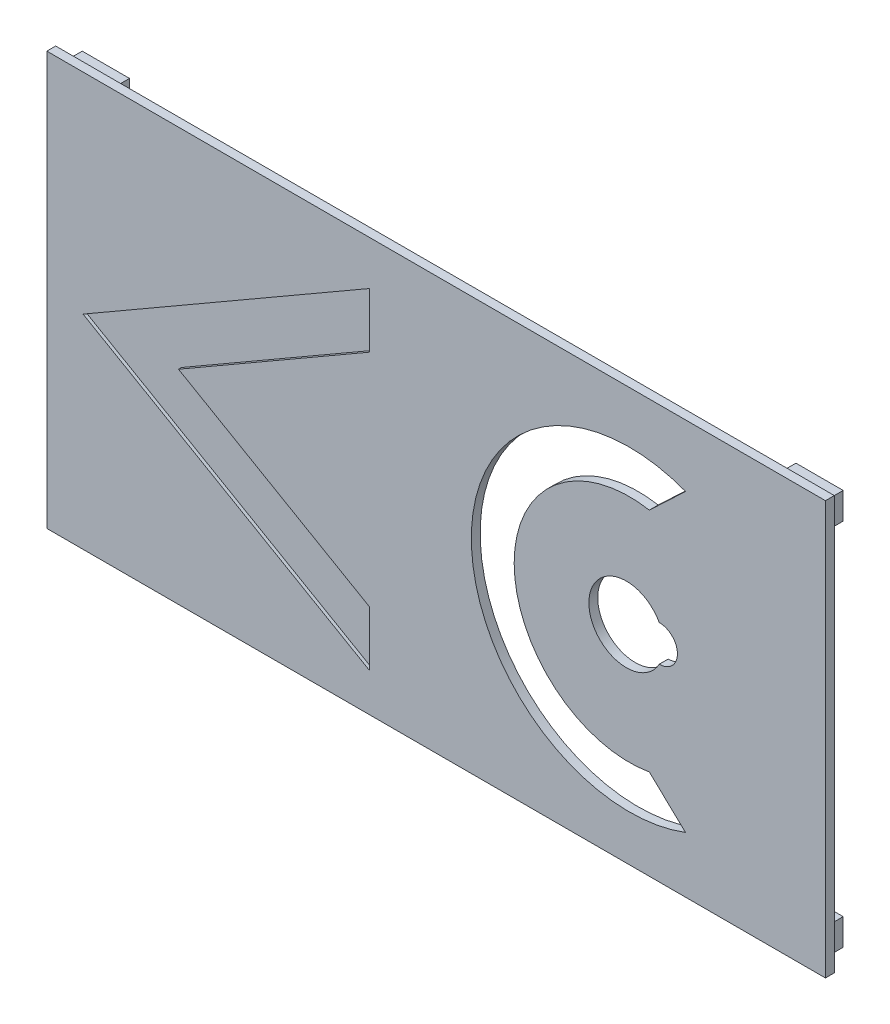
SolidWorks part; units mm, degrees
ref_plane "Front Plane" through (0, 0, 0) normal (0, 0, 1) x (1, 0, 0)
ref_plane "Top Plane" through (0, 0, 0) normal (0, 1, 0) x (1, 0, 0)
ref_plane "Right Plane" through (0, 0, 0) normal (1, 0, 0) x (0, 0, -1)
sketch "Sketch1" plane through (0, 0, 0) normal (0, 0, 1) x (1, 0, 0)
  line L0 (121.1, -9.75) -> (-10.75, -9.75)
  line L1 (119.6, -8.25) -> (-9.25, -8.25)
  line L2 (119.6, -8.25) -> (119.6, 58.75)
  line L3 (119.6, 58.75) -> (-9.25, 58.75)
  line L4 (-9.25, -8.25) -> (-9.25, 58.75)
  line L5 (-10.75, -9.75) -> (-10.75, 60.25)
  line L6 (121.1, 60.25) -> (-10.75, 60.25)
  line L7 (121.1, -9.75) -> (121.1, 60.25)
  dimension "D1" = 1.5
extrude "Boss-Extrude1" add sketch "Sketch1" along normal blind 1.5 contours L7 L6 L5 L0
sketch "Sketch2" plane through (0, 0, 1.5) normal (0, 0, 1) x (1, 0, 0)
  line L5 (92.9571, 22.2) -> (92.9875, 22.2)
  line L6 (92.9875, 28.3) -> (92.9571, 28.3)
  line L7 (92.9571, 22.2) -> (92.9875, 22.2)
  line L8 (92.9875, 28.3) -> (92.9571, 28.3)
  arc A10 (92.9875, 22.2) -> (92.9875, 28.3) centre (92.9875, 25.25) ccw
  arc A11 (92.9571, 28.3) -> (92.9571, 22.2) centre (87.3875, 25.25) ccw
  arc A12 (92.9875, 22.2) -> (92.9875, 28.3) centre (92.9875, 25.25) ccw
  arc A13 (92.9571, 28.3) -> (92.9571, 22.2) centre (87.3875, 25.25) ccw
  dimension "D1" = 0.25
extrude "Cut-Extrude1" cut sketch "Sketch2" against normal up to next
ref_plane "Plane2" through (0, 25.25, 0) normal (0, 1, 0) x (1, 0, 0)
ref_plane "Plane1" through (55.175, 0, 0) normal (1, 0, 0) x (0, 0, -1)
sketch "Sketch3" plane through (121.1, 0, 0) normal (1, 0, 0) x (0, 0, -1)
  line L0 (0, -9.75) -> (0, 60.25) construction
  line L1 (-1.5, 60.25) -> (6, 60.25)
  line L2 (-1.5, 60.25) -> (-1.5, 61.75)
  line L3 (-1.5, 61.75) -> (6, 61.75)
  line L4 (6, 60.25) -> (6, 61.75)
  line L5 (6, 60.25) -> (4.5, 58.75)
  line L7 (4.5, 58.75) -> (4.5, 60.25)
  dimension "D1" = 1.5
  dimension "D2" = 6
  dimension "D3" = 45
sketch "Sketch4" plane through (0, 0, 0) normal (0, 0, -1) x (-1, 0, 0)
  line L0 (-118.1, 57.25) -> (-118.1, 55.75)
  line L1 (-119.6, 58.75) -> (-111.6, 58.75)
  line L2 (-119.6, 58.75) -> (-119.6, 54.25)
  line L3 (-119.6, 54.25) -> (-111.6, 54.25)
  line L4 (-111.6, 58.75) -> (-111.6, 54.25)
  line L5 (-119.6, 58.75) -> (-119.6, 60.25) construction
  line L6 (-118.1, 55.75) -> (-113.1, 55.75)
  line L7 (-121.1, 60.25) -> (10.75, 60.25) construction
  line L8 (-113.1, 57.25) -> (-113.1, 55.75)
  line L9 (-118.1, 57.25) -> (-113.1, 57.25)
  line L10 (-119.6, 58.75) -> (-121.1, 58.75) construction
  line L11 (-121.1, -9.75) -> (-121.1, 60.25) construction
  dimension "D1" = 1.5
  dimension "D2" = 5
  dimension "D3" = 1.5
extrude "Boss-Extrude2" add sketch "Sketch4" along normal blind 3
mirror "Mirror1" about plane through (0, 25.25, 0) normal (0, 1, 0) of "Boss-Extrude2"
mirror "Mirror2" about plane through (55.175, 0, 0) normal (1, 0, 0) of "Mirror1", "Boss-Extrude2"
sketch "Sketch5" plane through (0, 0, 1.5) normal (0, 0, 1) x (1, 0, 0)
  line L0 (62.8875, 28.45) -> (62.8875, 21.05) construction
  line L1 (62.8875, 28.45) -> (62.8875, 21.05) construction
  line L2 (61.3875, 28.45) -> (61.3875, 21.05) construction
  line L3 (61.3875, 28.45) -> (61.3875, 21.05) construction
  line L4 (61.3875, 28.45) -> (62.8875, 28.45) construction
  line L5 (61.3875, 28.45) -> (62.8875, 28.45) construction
  line L6 (61.3875, 21.05) -> (62.8875, 21.05) construction
  line L7 (61.3875, 21.05) -> (62.8875, 21.05) construction
  line L8 (68.3875, 21.05) -> (66.8875, 21.05) construction
  line L9 (68.3875, 28.45) -> (66.8875, 28.45) construction
  line L10 (68.3875, 25.6038) -> (68.3875, 23.8962) construction
  line L11 (91.2742, 5.5464) -> (97.4081, -0.256)
  line L12 (61.3875, 21.05) -> (68.3875, 21.05) construction
  line L13 (61.3875, 21.05) -> (61.3875, 28.45) construction
  line L14 (61.3875, 28.45) -> (68.3875, 28.45) construction
  line L15 (68.3875, 21.05) -> (68.3875, 28.45) construction
  line L16 (84.1875, 51.25) -> (91.5875, 51.25) construction
  line L17 (84.1875, 51.25) -> (84.1875, 44.25) construction
  line L18 (84.1875, 44.25) -> (91.5875, 44.25) construction
  line L19 (91.5875, 51.25) -> (91.5875, 44.25) construction
  line L20 (68.3875, 21.05) -> (70.8875, 21.05)
  line L21 (70.8875, 21.05) -> (70.8875, 28.45)
  line L22 (70.8875, 28.45) -> (68.3875, 28.45)
  line L23 (68.3875, 28.45) -> (68.3875, 25.6038)
  line L24 (68.3875, 25.6038) -> (66.8875, 25.6038)
  line L25 (66.8875, 25.6038) -> (66.8875, 28.45)
  line L26 (66.8875, 28.45) -> (64.3875, 28.45)
  line L27 (64.3875, 28.45) -> (64.3875, 21.05)
  line L28 (64.3875, 21.05) -> (66.8875, 21.05)
  line L29 (66.8875, 21.05) -> (66.8875, 23.8962)
  line L30 (66.8875, 23.8962) -> (68.3875, 23.8962)
  line L31 (68.3875, 23.8962) -> (68.3875, 21.05)
  line L32 (84.1875, 51.25) -> (91.5875, 44.25) construction
  line L33 (84.1875, 44.25) -> (91.5875, 51.25) construction
  line L34 (84.1875, 5.25) -> (91.5875, 5.25) construction
  line L35 (68.3875, 28.45) -> (68.3875, 25.6038) construction
  line L36 (68.3875, 25.6038) -> (66.8875, 25.6038) construction
  line L37 (66.8875, 25.6038) -> (66.8875, 28.45) construction
  line L38 (84.1875, 5.25) -> (84.1875, -1.75) construction
  line L39 (84.1875, -1.75) -> (91.5875, -1.75) construction
  line L40 (91.5875, 5.25) -> (91.5875, -1.75) construction
  line L41 (66.8875, 21.05) -> (66.8875, 23.8962) construction
  line L42 (66.8875, 23.8962) -> (68.3875, 23.8962) construction
  line L43 (68.3875, 23.8962) -> (68.3875, 21.05) construction
  line L44 (84.1875, 5.25) -> (91.5875, -1.75) construction
  line L45 (84.1875, -1.75) -> (91.5875, 5.25) construction
  line L46 (91.2742, 43.9536) -> (97.4081, 49.756)
  arc A0 (97.4081, 49.756) -> (97.4081, -0.256) centre (87.8875, 24.75) ccw
  arc A1 (91.2742, 43.9536) -> (91.2742, 5.5464) centre (87.8875, 24.75) ccw
  point P19 (68.3875, 24.75)
  point P20 (87.8875, 47.75)
  point P25 (87.8875, 1.75)
  point P26 (87.8875, 44.25)
  point P32 (87.8875, 5.25)
  dimension "D1" = 0
extrude "Cut-Extrude2" cut sketch "Sketch5" against normal up to next
sketch "Sketch6" plane through (0, 0, 1.5) normal (0, 0, 1) x (1, 0, 0)
  line L0 (87.8875, 24.75) -> (43.8775, 24.75) construction
  line L1 (56.8875, -3.25) -> (43.8775, -3.25) construction
  line L2 (-4.6199, 24.75) -> (43.8775, -3.25)
  line L3 (43.8775, -3.25) -> (43.8775, 6.0833)
  line L4 (43.8775, 52.75) -> (-4.6199, 24.75)
  line L5 (43.8775, 6.0833) -> (43.8775, -3.25) construction
  line L6 (11.5459, 24.75) -> (43.8775, 6.0833)
  line L7 (43.8775, 24.75) -> (-4.6199, 24.75) construction
  line L8 (43.8775, 43.4167) -> (11.5459, 24.75)
  line L9 (43.8775, 43.4167) -> (43.8775, 52.75)
  line L10 (43.8775, 43.4167) -> (43.8775, 6.0833) construction
  line L11 (43.8775, 6.0833) -> (43.8775, -3.25) construction
  line L13 (43.8775, 25.25) -> (43.8775, 43.9167) [skipped]
  circle A0 centre (27.7117, 24.75) radius 16.1658 construction
  circle A1 centre (33.1003, 24.75) radius 10.7772 construction
  dimension "D1" = 44.01
extrude "Cut-Extrude3" cut sketch "Sketch6" against normal blind 0.5
equation "\"D1@Boss-Extrude2\"=1.50mm+.25"
